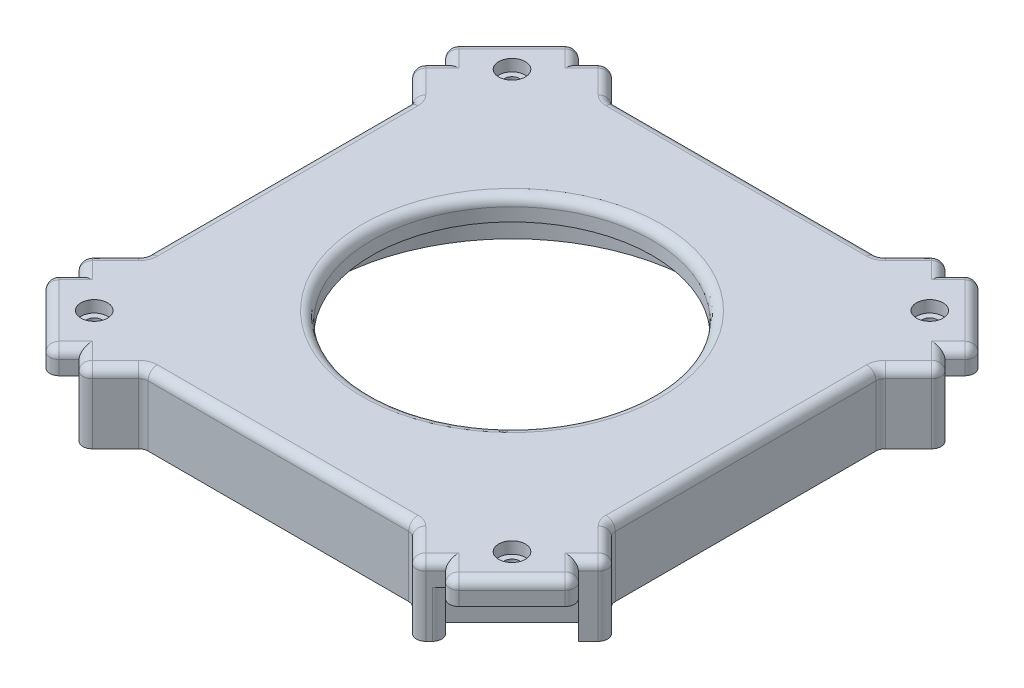
SolidWorks part; units mm, degrees
ref_plane "Front Plane" through (0, 0, 0) normal (0, 0, 1) x (1, 0, 0)
ref_plane "Top Plane" through (0, 0, 0) normal (0, 1, 0) x (1, 0, 0)
ref_plane "Right Plane" through (0, 0, 0) normal (1, 0, 0) x (0, 0, -1)
sketch "Sketch1" plane through (0, 0, 0) normal (0, 1, 0) x (1, 0, 0)
  line L1 (-50, -50) -> (50, -50)
  line L2 (-50, -50) -> (-50, 50)
  line L3 (-50, 50) -> (50, 50)
  line L4 (50, -50) -> (50, 50)
  line L5 (-50, -50) -> (50, 50) construction
  line L6 (-50, 50) -> (50, -50) construction
  point P0 (0, 0)
  dimension "D1" = 100
extrude "Boss-Extrude1" add sketch "Sketch1" along normal blind 15 contours L1 L4 L3 L2
sketch "Sketch2" plane through (0, 0, 0) normal (0, -1, 0) x (1, 0, 0)
  circle A0 centre (0, 0) radius 40
  dimension "D1" = 80
extrude "Cut-Extrude1" cut sketch "Sketch2" against normal blind 10.2 contours A0
sketch "Sketch3" plane through (0, 10.2, 0) normal (0, -1, 0) x (1, 0, 0)
  circle A0 centre (0, 0) radius 30
  dimension "D1" = 60
extrude "Cut-Extrude2" cut sketch "Sketch3" against normal up to next
ref_plane "Plane1" through (0, 0, 0) normal (0.7071, 0, -0.7071) x (-0.7071, 0, -0.7071)
sketch "Sketch4" plane through (0, 0, 0) normal (0.7071, 0, -0.7071) x (-0.7071, 0, -0.7071)
  line L0 (-70.7107, 0) -> (0, 0) construction
  line L1 (-70.7107, 15) -> (-60.5107, 15)
  line L2 (-70.7107, 15) -> (-70.7107, 0)
  line L3 (-70.7107, 0) -> (-60.5107, 0)
  line L4 (-60.5107, 15) -> (-60.5107, 0)
  dimension "D1" = 10.2
extrude "Cut-Extrude3" cut sketch "Sketch4" against normal up to next and the other way up to next
pattern_circular "CirPattern1" count 4 every 90 about axis through (0, 0, 0) along (0, 1, 0) of "Cut-Extrude3"
sketch "Sketch5" plane through (0, 15, 0) normal (0, 1, 0) x (1, 0, 0)
  line L0 (-49.8939, 35.6811) -> (-53.4295, 39.2166)
  line L1 (-53.4295, 39.2166) -> (-56.965, 35.6811)
  line L2 (-56.965, 35.6811) -> (-50, 28.7161)
  line L3 (-50, -35.575) -> (-50, 35.575) construction
  line L6 (-50, 35.575) -> (-35.575, 50) construction
  line L7 (5.8336, -5.8336) -> (-5.8336, 5.8336) construction
  line L8 (-39.2166, 53.4295) -> (-35.6811, 56.965)
  line L9 (-35.6811, 56.965) -> (-28.7161, 50)
  line L10 (-28.7161, 50) -> (-35.6811, 49.8939)
  line L11 (-35.6811, 49.8939) -> (-39.2166, 53.4295)
  line L12 (35.6811, 49.8939) -> (39.2166, 53.4295)
  line L13 (39.2166, 53.4295) -> (35.6811, 56.965)
  line L14 (35.6811, 56.965) -> (28.7161, 50)
  line L15 (28.7161, 50) -> (35.6811, 49.8939)
  line L16 (49.8939, 35.6811) -> (53.4295, 39.2166)
  line L17 (53.4295, 39.2166) -> (56.965, 35.6811)
  line L18 (56.965, 35.6811) -> (50, 28.7161)
  line L19 (50, 28.7161) -> (49.8939, 35.6811)
  line L20 (49.8939, -35.6811) -> (53.4295, -39.2166)
  line L21 (53.4295, -39.2166) -> (56.965, -35.6811)
  line L22 (56.965, -35.6811) -> (50, -28.7161)
  line L23 (50, -28.7161) -> (49.8939, -35.6811)
  line L24 (35.6811, -49.8939) -> (39.2166, -53.4295)
  line L25 (39.2166, -53.4295) -> (35.6811, -56.965)
  line L26 (35.6811, -56.965) -> (28.7161, -50)
  line L27 (28.7161, -50) -> (35.6811, -49.8939)
  line L28 (-35.6811, -49.8939) -> (-39.2166, -53.4295)
  line L29 (-39.2166, -53.4295) -> (-35.6811, -56.965)
  line L30 (-35.6811, -56.965) -> (-28.7161, -50)
  line L31 (-28.7161, -50) -> (-35.6811, -49.8939)
  line L32 (-49.8939, -35.6811) -> (-53.4295, -39.2166)
  line L33 (-53.4295, -39.2166) -> (-56.965, -35.6811)
  line L34 (-56.965, -35.6811) -> (-50, -28.7161)
  line L35 (-50, -28.7161) -> (-49.8939, -35.6811)
  line L36 (-50, 28.7161) -> (-50, 35.575)
  line L37 (-50, 35.575) -> (-49.8939, 35.6811)
  point P0 (-49.4251, 36.1499)
  point P16 (0, 0)
  point P18 (-49.1154, 36.4773)
  point P43 (0, 0)
  dimension "D1" = 0.15
  dimension "D2" = 5
  dimension "D3" = 5
  dimension "D4" = 4
extrude "Boss-Extrude2" add sketch "Sketch5" against normal up to surface (15 mm away) up to face at (0, 0, -40)
sketch "Sketch6" plane through (42.7875, 0, 42.7875) normal (0.7071, 0, 0.7071) x (0.7071, 0, -0.7071)
  line L1 (-10.05, 15) -> (10.05, 15)
  line L2 (-10.05, 15) -> (-10.05, 10)
  line L3 (-10.05, 10) -> (10.05, 10)
  line L4 (10.05, 15) -> (10.05, 10)
  line L5 (10.05, 0) -> (10.05, 15) construction
  point P4 (10.05, 9.553)
  dimension "D1" = 5
extrude "Boss-Extrude3" add sketch "Sketch6" along normal blind 10
pattern_circular "CirPattern2" count 4 every 90 about axis through (0, 0, 0) along (0, 1, 0) of "Boss-Extrude3"
sketch "Sketch7" plane through (0, 15, 0) normal (0, 1, 0) x (1, 0, 0)
  line L0 (49.8939, 35.6811) -> (35.6811, 49.8939) construction
  line L1 (49.8586, 49.8586) -> (0, 0) construction
  line L2 (42.7522, 56.965) -> (56.965, 42.7522) construction
  circle A0 centre (44.6967, 44.6967) radius 1.6
  point P2 (0, 0)
  dimension "D1" = 3.2
  dimension "D2" = 2.7
extrude "Cut-Extrude4" cut sketch "Sketch7" against normal up to next contours A0
sketch "Sketch8" plane through (0, 15, 0) normal (0, 1, 0) x (1, 0, 0)
  circle A0 centre (44.6967, 44.6967) radius 2.85
  circle A1 centre (44.6967, 44.6967) radius 1.6 construction
  dimension "D1" = 5.7
extrude "Cut-Extrude5" cut sketch "Sketch8" against normal blind 2.5
pattern_circular "CirPattern3" count 4 every 90 about axis through (0, 0, 0) along (0, 1, 0) of "Cut-Extrude5", "Cut-Extrude4"
fillet "Fillet1" radius 2 57 edges at (32.1986, 15, -53.4825) (37.4489, 15, -55.1972) (35.6811, 7.5, -56.965) (28.7161, 7.5, -50) (53.4825, 15, -32.1986) (55.1972, 15, -37.4489) (50, 7.5, -28.7161) (56.965, 7.5, -35.6811) (55.1972, 15, 37.4489) (53.4825, 15, 32.1986) (56.965, 7.5, 35.6811) (50, 7.5, 28.7161) (32.1986, 15, 53.4825) (37.4489, 15, 55.1972) (28.7161, 7.5, 50) (35.6811, 7.5, 56.965) (-37.4489, 15, 55.1972) (-32.1986, 15, 53.4825) (-35.6811, 7.5, 56.965) (-28.7161, 7.5, 50) (-53.4825, 15, 32.1986) (-55.1972, 15, 37.4489) (-50, 7.5, 28.7161) (-56.965, 7.5, 35.6811) (-55.1972, 15, -37.4489) (-53.4825, 15, -32.1986) (-50, 7.5, -28.7161) (-56.965, 7.5, -35.6811) (40.9844, 15, 55.1972) (55.1972, 15, 40.9844) (42.7522, 12.5, 56.965) (56.965, 12.5, 42.7522) (49.8586, 15, 49.8586) (55.1972, 15, -40.9844) (40.9844, 15, -55.1972) (56.965, 12.5, -42.7522) (42.7522, 12.5, -56.965) (49.8586, 15, -49.8586) (-40.9844, 15, -55.1972) (-55.1972, 15, -40.9844) (-42.7522, 12.5, -56.965) (-56.965, 12.5, -42.7522) (-49.8586, 15, -49.8586) (0, 15, -30) (-55.1972, 15, 40.9844) (-40.9844, 15, 55.1972) (-56.965, 12.5, 42.7522) (-42.7522, 12.5, 56.965) (-49.8586, 15, 49.8586) (0, 15, -50) (-50, 15, 0) (0, 15, 50) (50, 15, 0) (-32.1986, 15, -53.4825) (-37.4489, 15, -55.1972) (-28.7161, 7.5, -50) (-35.6811, 7.5, -56.965)
